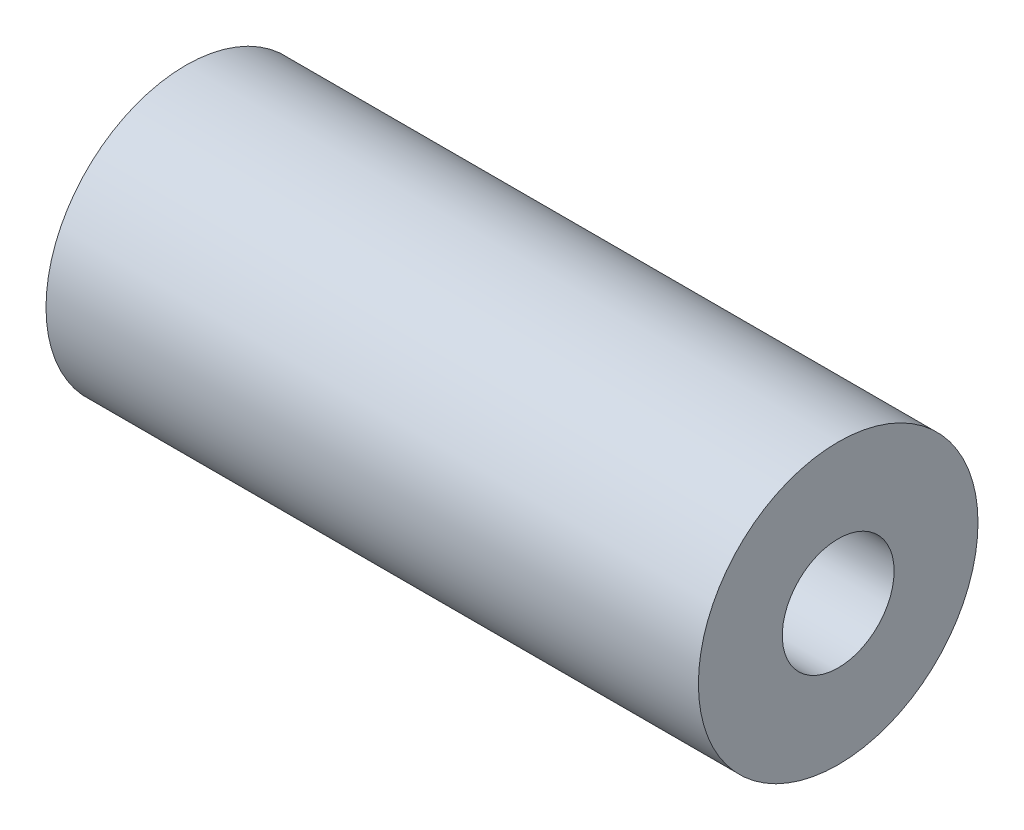
SolidWorks part; units mm, degrees
ref_plane "Alzado" through (0, 0, 0) normal (0, 0, 1) x (1, 0, 0)
ref_plane "Planta" through (0, 0, 0) normal (0, 1, 0) x (1, 0, 0)
ref_plane "Vista lateral" through (0, 0, 0) normal (1, 0, 0) x (0, 0, -1)
sketch "Croquis1" plane through (0, 0, 0) normal (1, 0, 0) x (0, 0, -1)
  circle A0 centre (0, 0) radius 60
  circle A1 centre (0, 0) radius 24
extrude "Saliente-Extruir1" add sketch "Croquis1" along normal blind 280
